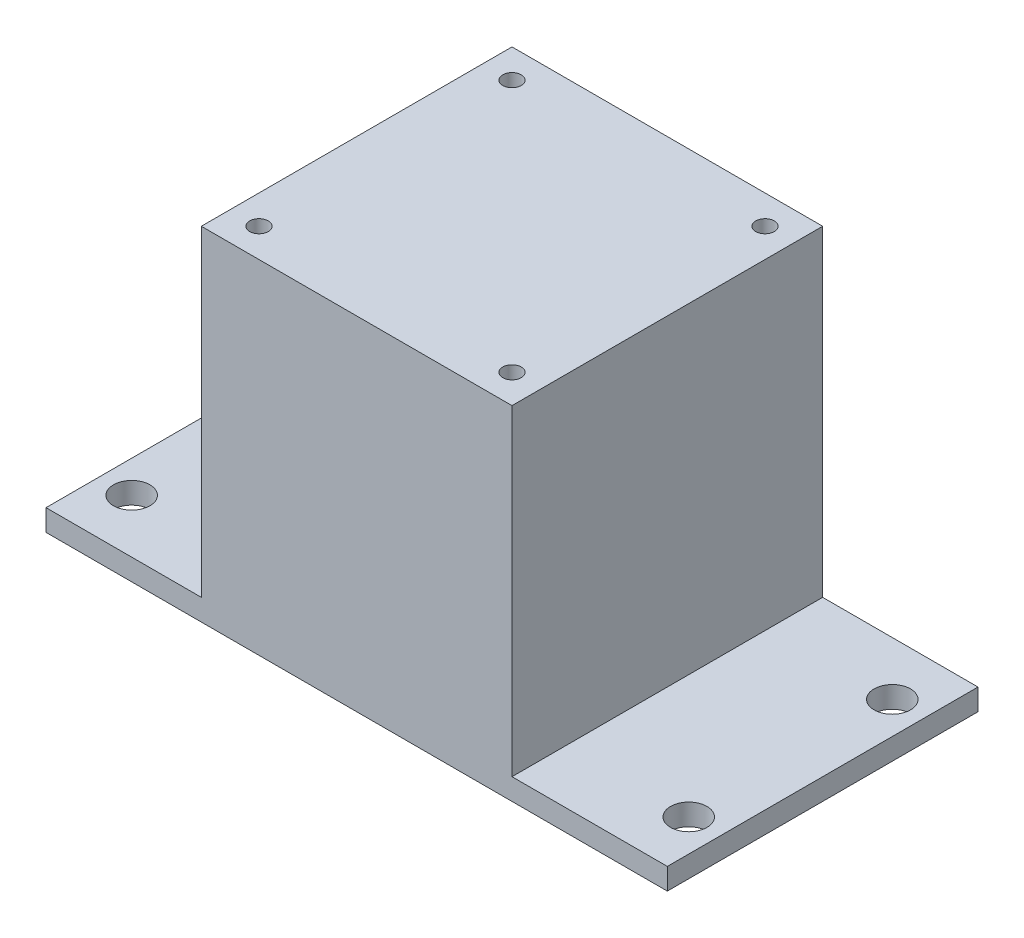
SolidWorks part; units mm, degrees
ref_plane "Front Plane" through (0, 0, 0) normal (0, 0, 1) x (1, 0, 0)
ref_plane "Top Plane" through (0, 0, 0) normal (0, 1, 0) x (1, 0, 0)
ref_plane "Right Plane" through (0, 0, 0) normal (1, 0, 0) x (0, 0, -1)
sketch "Sketch1" plane through (0, 0, 0) normal (0, 1, 0) x (1, 0, 0)
  line L0 (-1.4225, 15.1389) -> (-1.4225, -32.1148) construction
  line L1 (-38.2525, 15.1389) -> (35.4075, 15.1389)
  line L2 (-38.2525, 15.1389) -> (-38.2525, -21.6911)
  line L3 (-38.2525, -21.6911) -> (35.4075, -21.6911)
  line L4 (35.4075, 15.1389) -> (35.4075, -21.6911)
  line L5 (35.4075, -3.2761) -> (-38.4515, -3.2761) construction
  circle A0 centre (-16.4225, 11.7239) radius 1.1
  circle A1 centre (13.5775, 11.7239) radius 1.1
  circle A2 centre (13.5775, -18.2761) radius 1.1
  circle A3 centre (-16.4225, -18.2761) radius 1.1
  circle A4 centre (31.5975, -15.3411) radius 2.159
  circle A5 centre (31.5975, 8.7889) radius 2.159
  circle A6 centre (-34.4425, -15.3411) radius 2.159
  circle A7 centre (-34.4425, 8.7889) radius 2.159
  dimension "D3" = 2.2
  dimension "D4" = 30
  dimension "D6" = 4.318
  dimension "D1" = 73.66
  dimension "D2" = 36.83
  dimension "D5" = 30
  dimension "D7" = 33.02
  dimension "D8" = 24.13
extrude "Boss-Extrude1" add sketch "Sketch1" along normal blind 40.64
sketch "Sketch3" plane through (0, 0, 0) normal (0, -1, 0) x (1, 0, 0)
  line L0 (-1.4225, 21.6911) -> (-1.4225, -15.1389) construction
  line L1 (-38.2525, 21.6911) -> (35.4075, 21.6911) construction
  line L2 (35.4075, -15.1389) -> (-38.2525, -15.1389) construction
  line L3 (35.4075, 3.2761) -> (-38.2525, 3.2761) construction
  line L4 (35.4075, 21.6911) -> (35.4075, -15.1389) construction
  line L5 (-38.2525, -15.1389) -> (-38.2525, 21.6911) construction
  circle A0 centre (-16.4225, 18.2761) radius 2.54
  circle A1 centre (-16.4225, 18.2761) radius 1.1 construction
  circle A2 centre (13.5775, 18.2761) radius 2.54
  circle A3 centre (13.5775, -11.7239) radius 2.54
  circle A4 centre (-16.4225, -11.7239) radius 2.54
  dimension "D1" = 5.08
extrude "Cut-Extrude2" cut sketch "Sketch3" against normal blind 38.1
sketch "Sketch4" plane through (0, 40.64, 0) normal (0, 1, 0) x (1, 0, 0)
  line L0 (-38.2525, -21.6911) -> (35.4075, -21.6911) construction
  line L1 (-38.2525, 15.1389) -> (-19.8375, 15.1389)
  line L2 (-38.2525, 15.1389) -> (-38.2525, -21.6911)
  line L3 (-38.2525, -21.6911) -> (-19.8375, -21.6911)
  line L4 (-19.8375, 15.1389) -> (-19.8375, -21.6911)
  line L6 (35.4075, 15.1389) -> (16.9925, 15.1389)
  line L7 (35.4075, 15.1389) -> (35.4075, -21.6911)
  line L8 (35.4075, -21.6911) -> (16.9925, -21.6911)
  line L9 (16.9925, 15.1389) -> (16.9925, -21.6911)
  dimension "D1" = 36.83
extrude "Cut-Extrude3" cut sketch "Sketch4" against normal blind 38.1
sketch "Sketch5" plane through (0, 0, 0) normal (0, -1, 0) x (1, 0, 0)
  line L0 (9.7675, 14.4661) -> (13.5775, 14.4661)
  line L1 (-12.6125, 18.2761) -> (9.7675, 18.2761)
  line L2 (-12.6125, 18.2761) -> (-12.6125, 14.4661)
  line L3 (-12.6125, -11.7239) -> (9.7675, -11.7239)
  line L4 (9.7675, 18.2761) -> (9.7675, 14.4661)
  line L5 (-16.4225, 14.4661) -> (-12.6125, 14.4661)
  line L6 (-16.4225, 14.4661) -> (-16.4225, -7.9139)
  line L7 (-16.4225, -7.9139) -> (-12.6125, -7.9139)
  line L8 (13.5775, 14.4661) -> (13.5775, -7.9139)
  line L9 (-12.6125, -7.9139) -> (-12.6125, -11.7239)
  line L10 (9.7675, -7.9139) -> (13.5775, -7.9139)
  line L11 (9.7675, -7.9139) -> (9.7675, -11.7239)
  circle A1 centre (13.5775, -11.7239) radius 2.54 construction
  circle A2 centre (-16.4225, -11.7239) radius 2.54 construction
  circle A3 centre (13.5775, 18.2761) radius 2.54 construction
  circle A4 centre (-16.4225, 18.2761) radius 2.54 construction
  circle A5 centre (13.5775, -11.7239) radius 2.54
  circle A6 centre (-16.4225, -11.7239) radius 2.54
  circle A7 centre (13.5775, 18.2761) radius 2.54
  circle A8 centre (-16.4225, 18.2761) radius 2.54
  dimension "D1" = 3.81
  dimension "D2" = 3.81
  dimension "D3" = 3.81
  dimension "D4" = 3.81
extrude "Cut-Extrude4" [suppressed] cut sketch "Sketch5" against normal blind 38.1 contours L11 L10 L8 L0 L4 L1 L2 L5 L6 L7 L9 L3
